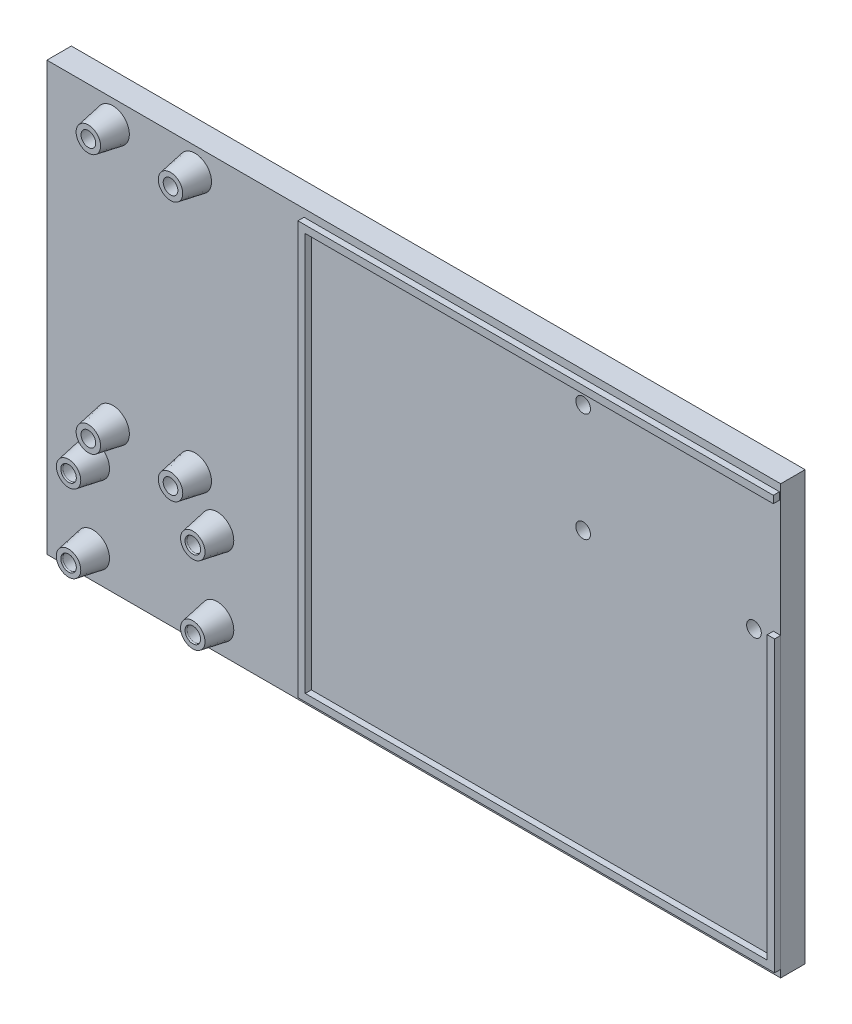
SolidWorks part; units mm, degrees
ref_plane "Front Plane" through (0, 0, 0) normal (0, 0, 1) x (1, 0, 0)
ref_plane "Top Plane" through (0, 0, 0) normal (0, 1, 0) x (1, 0, 0)
ref_plane "Right Plane" through (0, 0, 0) normal (1, 0, 0) x (0, 0, -1)
sketch "Sketch1" plane through (0, 0, 0) normal (0, 0, 1) x (1, 0, 0)
  line L1 (-60, -35) -> (60, -35)
  line L2 (-60, -35) -> (-60, 35)
  line L3 (-60, 35) -> (60, 35)
  line L4 (60, -35) -> (60, 35)
  line L5 (-60, -35) -> (60, 35) construction
  line L6 (-60, 35) -> (60, -35) construction
  point P0 (0, 0)
  dimension "D1" = 70
  dimension "D2" = 120
extrude "Boss-Extrude1" add sketch "Sketch1" along normal blind 4
sketch "Sketch2" plane through (0, 0, 4) normal (0, 0, 1) x (1, 0, 0)
  line L0 (31.252, 12.2555) -> (55.636, 12.2555) construction
  line L1 (-16.5, 32.3215) -> (58.557, 32.3215)
  line L2 (-16.5, 32.3215) -> (-16.5, -32.3215)
  line L3 (-16.5, -32.3215) -> (58.557, -32.3215)
  line L4 (58.557, 32.3215) -> (58.557, -32.3215)
  line L5 (31.252, 13.5255) -> (55.636, 13.5255)
  line L6 (31.252, 10.9855) -> (55.636, 10.9855)
  line L7 (27.696, 12.2555) -> (27.696, 30.0355) construction
  line L8 (0, 0) -> (-16.5, 0) construction
  line L9 (-42.3, -15.22) -> (-42.3, -33) construction
  line L10 (-55, -15.22) -> (-29.6, -15.22)
  line L11 (-55, -15.22) -> (-55, -33)
  line L12 (-55, -33) -> (-29.6, -33)
  line L13 (-29.6, -15.22) -> (-29.6, -33)
  line L14 (-60, 35) -> (-60, -35) construction
  line L15 (-52.46, -30.46) -> (-32.14, -30.46)
  line L16 (-52.46, -30.46) -> (-52.46, -17.76)
  line L17 (-52.46, -17.76) -> (-32.14, -17.76)
  line L18 (-32.14, -30.46) -> (-32.14, -17.76)
  line L19 (-52.46, -30.46) -> (-32.14, -17.76) construction
  line L20 (-52.46, -17.76) -> (-32.14, -30.46) construction
  line L21 (-50, 32) -> (-35, 32)
  line L22 (-50, 32) -> (-50, -12)
  line L23 (-50, -12) -> (-35, -12)
  line L24 (-35, 32) -> (-35, -12)
  line L25 (-60, -35) -> (60, -35) construction
  line L26 (60, 35) -> (-60, 35) construction
  line L27 (-42.5, 32) -> (-42.5, -12) construction
  line L28 (-49.22, 31.22) -> (-49.22, 32)
  line L29 (-35.78, 31.22) -> (-49.22, 31.22)
  line L30 (-35.78, 31.22) -> (-35.78, -11.22)
  line L31 (-35.78, -11.22) -> (-49.22, -11.22)
  line L32 (-49.22, 31.22) -> (-49.22, -11.22)
  line L33 (-35.78, 31.22) -> (-49.22, -11.22) construction
  line L34 (-35.78, -11.22) -> (-49.22, 31.22) construction
  line L35 (-49.22, 31.22) -> (-50, 31.22)
  arc A0 (31.252, 13.5255) -> (31.252, 10.9855) centre (31.252, 12.2555) ccw
  arc A1 (55.636, 10.9855) -> (55.636, 13.5255) centre (55.636, 12.2555) ccw
  circle A2 centre (27.696, 12.2555) radius 1.27
  circle A3 centre (27.696, 30.0355) radius 1.27
  circle A4 centre (-52.46, -17.76) radius 1.27
  circle A5 centre (-32.14, -17.76) radius 1.27
  circle A6 centre (-52.46, -30.46) radius 1.27
  circle A7 centre (-32.14, -30.46) radius 1.27
  point P6 (43.444, 12.2555)
  point P24 (-42.3, -24.11)
  point P45 (-42.5, 10)
  dimension "D5" = 2.54
  dimension "D14" = 2.54
  dimension "D1" = 75.057
  dimension "D2" = 64.643
  dimension "D3" = 44.196
  dimension "D4" = 44.577
  dimension "D6" = 62.357
  dimension "D7" = 47.752
  dimension "D8" = 72.136
  dimension "D9" = 16.5
  dimension "D10" = 25.4
  dimension "D11" = 17.78
  dimension "D12" = 20.32
  dimension "D13" = 12.7
  dimension "D15" = 15
  dimension "D16" = 44
  dimension "D17" = 10
  dimension "D18" = 5
  dimension "D19" = 2
  dimension "D20" = 3
  dimension "D21" = 0.78
sketch "Sketch3" plane through (0, 0, 4) normal (0, 0, 1) x (1, 0, 0)
  line L0 (31.252, 13.5255) -> (55.636, 13.5255) construction
  line L4 (59.807, 33.7715) -> (-17.95, 33.7715)
  line L5 (-17.95, 33.7715) -> (-17.95, -33.7715)
  line L6 (-17.95, -33.7715) -> (60.007, -33.7715)
  line L7 (60.007, -33.7715) -> (60.007, 13.5255)
  line L8 (-16.75, 32.5715) -> (-16.75, -32.5715)
  line L9 (-16.75, -32.5715) -> (58.807, -32.5715)
  line L10 (58.807, -32.5715) -> (58.807, 32.5715)
  line L11 (58.807, 32.5715) -> (-16.75, 32.5715)
  line L12 (-16.75, 32.5715) -> (-16.75, -32.5715) construction
  line L13 (-16.75, -32.5715) -> (58.807, -32.5715) construction
  line L14 (58.807, -32.5715) -> (58.807, 32.5715) construction
  line L15 (58.807, 32.5715) -> (-16.75, 32.5715) construction
  line L16 (60.007, 13.5255) -> (58.807, 13.5255)
  line L17 (58.807, 13.5255) -> (58.807, -32.5715)
  line L18 (58.807, -32.5715) -> (-16.75, -32.5715)
  line L19 (-16.75, -32.5715) -> (-16.75, 32.5715)
  line L20 (-16.75, 32.5715) -> (59.807, 32.5715)
  line L21 (59.807, 32.5715) -> (59.807, 33.7715)
  line L22 (-16.75, -32.5715) -> (-17.95, -32.5715) construction
  line L23 (-16.75, -32.5715) -> (-16.75, -33.7715) construction
  dimension "D2" = 1.2
  dimension "D3" = 1
  dimension "D1" = 0.25
extrude "Boss-Extrude3" add sketch "Sketch3" along normal blind 1
sketch "Sketch4" plane through (0, 0, 4) normal (0, 0, 1) x (1, 0, 0)
  circle A0 centre (-52.46, -30.46) radius 1.27 construction
  circle A1 centre (-32.14, -30.46) radius 1.27 construction
  circle A2 centre (-32.14, -17.76) radius 1.27 construction
  circle A3 centre (-52.46, -17.76) radius 1.27 construction
  circle A4 centre (-52.46, -30.46) radius 1.27
  circle A5 centre (-32.14, -30.46) radius 1.27
  circle A6 centre (-32.14, -17.76) radius 1.27
  circle A7 centre (-52.46, -17.76) radius 1.27
  circle A8 centre (-52.46, -17.76) radius 2
  circle A9 centre (-32.14, -17.76) radius 2
  circle A10 centre (-52.46, -30.46) radius 2
  circle A11 centre (-32.14, -30.46) radius 2
  circle A12 centre (-49.22, 31.22) radius 2
  circle A13 centre (-35.78, 31.22) radius 2
  circle A14 centre (-49.22, 31.22) radius 1.1
  circle A15 centre (-35.78, 31.22) radius 1.1
  circle A16 centre (-49.22, -11.22) radius 2
  circle A17 centre (-35.78, -11.22) radius 2
  circle A18 centre (-49.22, -11.22) radius 1.1
  circle A19 centre (-35.78, -11.22) radius 1.1
  dimension "D1" = 4
  dimension "D2" = 2.2
  dimension "D3" = 4
extrude "Boss-Extrude4" add sketch "Sketch4" against normal blind 5 draft 10 from offset 4 draft outward yes
sketch "Sketch5" plane through (0, 0, 8) normal (0, 0, 1) x (1, 0, 0)
  circle A8 centre (-52.46, -17.76) radius 1.2
  circle A9 centre (-32.14, -17.76) radius 1.2
  circle A10 centre (-52.46, -30.46) radius 1.2
  circle A11 centre (-32.14, -30.46) radius 1.2
  circle A12 centre (-49.22, 31.22) radius 1.2
  circle A13 centre (-35.78, 31.22) radius 1.2
  circle A14 centre (-49.22, -11.22) radius 1.2
  circle A15 centre (-35.78, -11.22) radius 1.2
  dimension "D1" = 2.4
  dimension "D2" = 2.4
extrude "Cut-Extrude1" cut sketch "Sketch5" against normal through all draft 4 draft outward yes
sketch "Sketch6" plane through (0, 0, 4) normal (0, 0, 1) x (1, 0, 0)
  circle A0 centre (27.696, 30.0355) radius 1.2
  circle A1 centre (27.696, 12.2555) radius 1.2
  circle A2 centre (55.636, 12.2555) radius 1.2
  dimension "D1" = 2.4
extrude "Cut-Extrude2" cut sketch "Sketch6" against normal through all draft 5 draft outward yes
equation "\"D3@Sketch2\"=1740mil"
equation "\"D4@Sketch2\"=1755mil"
equation "\"D5@Sketch2\"=100mil"
equation "\"D6@Sketch2\"=2455mil"
equation "\"D7@Sketch2\"=1880mil"
equation "\"D8@Sketch2\"=2840mil"
equation "\"D10@Sketch2\"=1in"
equation "\"D11@Sketch2\"=0.7in"
equation "\"D12@Sketch2\"=.8in"
equation "\"D13@Sketch2\"=.5in"
equation "\"D14@Sketch2\"=.1in"
equation "\"D21@Sketch2\"=.78"
